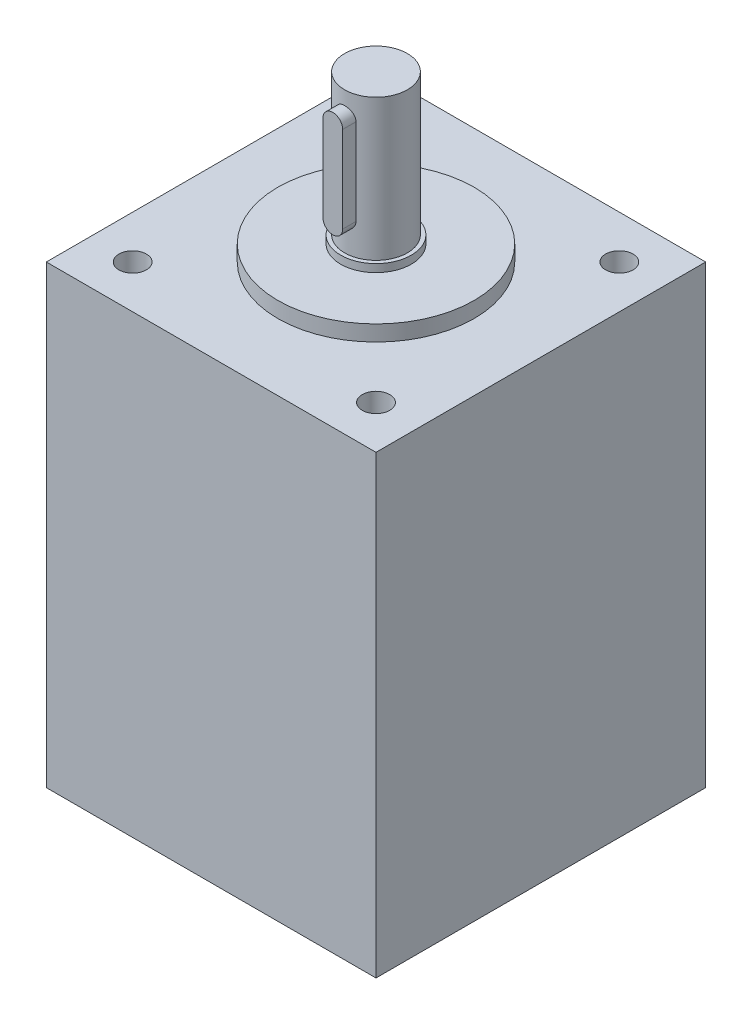
SolidWorks part; units mm, degrees
ref_plane "前视基准面" through (0, 0, 0) normal (0, 0, 1) x (1, 0, 0)
ref_plane "上视基准面" through (0, 0, 0) normal (0, 1, 0) x (1, 0, 0)
ref_plane "右视基准面" through (0, 0, 0) normal (1, 0, 0) x (0, 0, -1)
other "Configuration Table"
sketch "草图2" plane through (0, 0, 0) normal (0, 1, 0) x (1, 0, 0)
  line L1 (0, 0) -> (42, 0)
  line L2 (0, 0) -> (0, 42)
  line L3 (0, 42) -> (42, 42)
  line L4 (42, 0) -> (42, 42)
  dimension "D1" = 42
  dimension "D2" = 42
extrude "凸台-拉伸1" add sketch "草图2" along normal blind 58
sketch "草图3" plane through (0, 58, 0) normal (0, 1, 0) x (1, 0, 0)
  circle A0 centre (21, 21) radius 12.5
extrude "凸台-拉伸2" add sketch "草图3" along normal blind 2
sketch "草图4" plane through (0, 60, 0) normal (0, 1, 0) x (1, 0, 0)
  circle A0 centre (21, 21) radius 4.5
extrude "凸台-拉伸3" add sketch "草图4" along normal blind 1
sketch "草图5" plane through (0, 61, 0) normal (0, 1, 0) x (1, 0, 0)
  circle A0 centre (21, 21) radius 4
extrude "凸台-拉伸4" add sketch "草图5" along normal blind 18
ref_plane "基准面1" through (0, 0, -17) normal (0, 0, 1) x (1, 0, 0)
sketch "草图6" plane through (0, 0, -17) normal (0, 0, 1) x (1, 0, 0)
  line L0 (21, 79) -> (21, -49921) construction
  line L1 (25, 79) -> (17, 79) construction
  line L2 (21, 76) -> (21, 65) construction
  line L3 (22.2549, 76) -> (22.2549, 65)
  line L4 (19.7451, 76) -> (19.7451, 65)
  arc A0 (22.2549, 76) -> (19.7451, 76) centre (21, 76) ccw
  arc A1 (19.7451, 65) -> (22.2549, 65) centre (21, 65) ccw
  point P4 (21, 79)
  point P7 (21, 70.5)
  dimension "D1" = 3
  dimension "D2" = 11
extrude "凸台-拉伸5" add sketch "草图6" along normal blind 1.5 and the other way blind 4
sketch "草图7" plane through (0, 58, 0) normal (0, 1, 0) x (1, 0, 0)
  line L0 (42, 42) -> (0, 42) construction
  line L1 (0, 42) -> (0, 0) construction
  line L2 (21, 21) -> (21, 50021) construction
  line L3 (21, 21) -> (50021, 21) construction
  circle A0 centre (5.5, 36.5) radius 1.75
  circle A1 centre (36.5, 36.5) radius 1.75
  circle A2 centre (36.5, 5.5) radius 1.75
  circle A3 centre (5.5, 5.5) radius 1.75
  dimension "D1" = 3.5
  dimension "D2" = 5.5
  dimension "D3" = 5.5
extrude "切除-拉伸1" cut sketch "草图7" against normal blind 71.5
